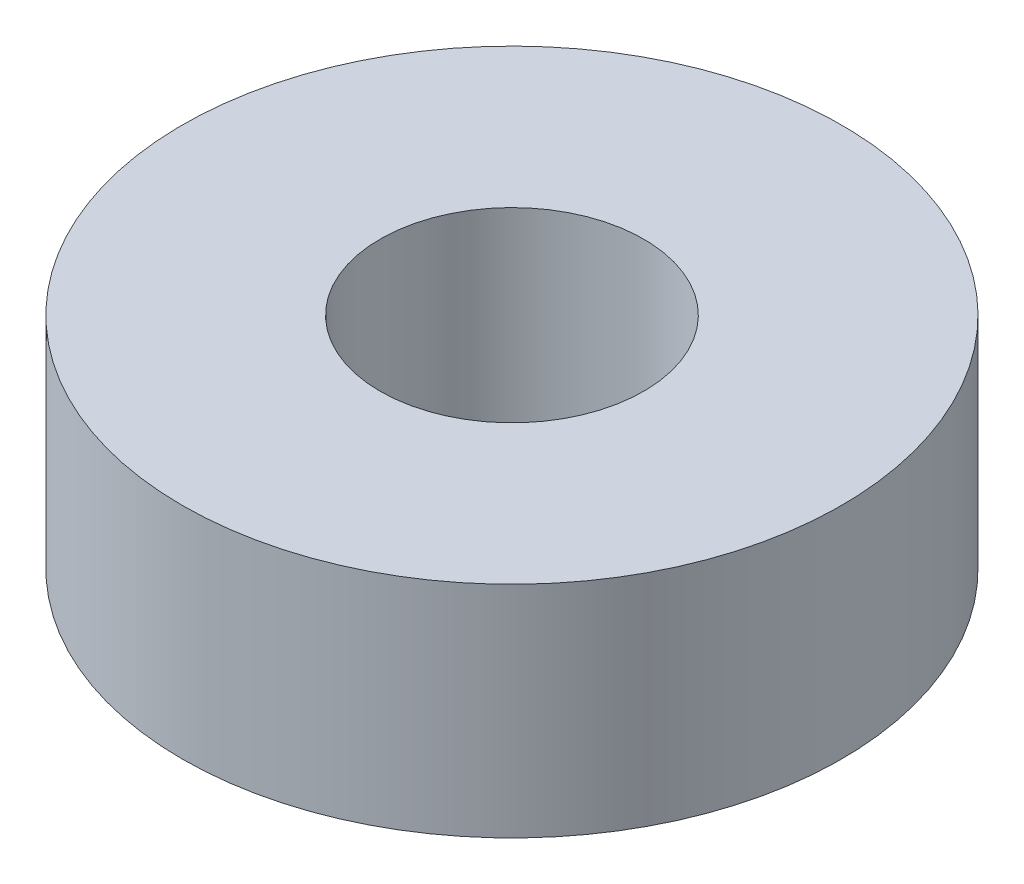
SolidWorks part; units mm, degrees
ref_plane "Спереди" through (0, 0, 0) normal (0, 0, 1) x (1, 0, 0)
ref_plane "Сверху" through (0, 0, 0) normal (0, 1, 0) x (1, 0, 0)
ref_plane "Справа" through (0, 0, 0) normal (1, 0, 0) x (0, 0, -1)
sketch "Эскиз1" plane through (0, 0, 0) normal (0, 1, 0) x (1, 0, 0)
  circle A0 centre (0, 0) radius 7.5
  circle A1 centre (0, 0) radius 3
extrude "Вытянуть1" add sketch "Эскиз1" along normal blind 5
